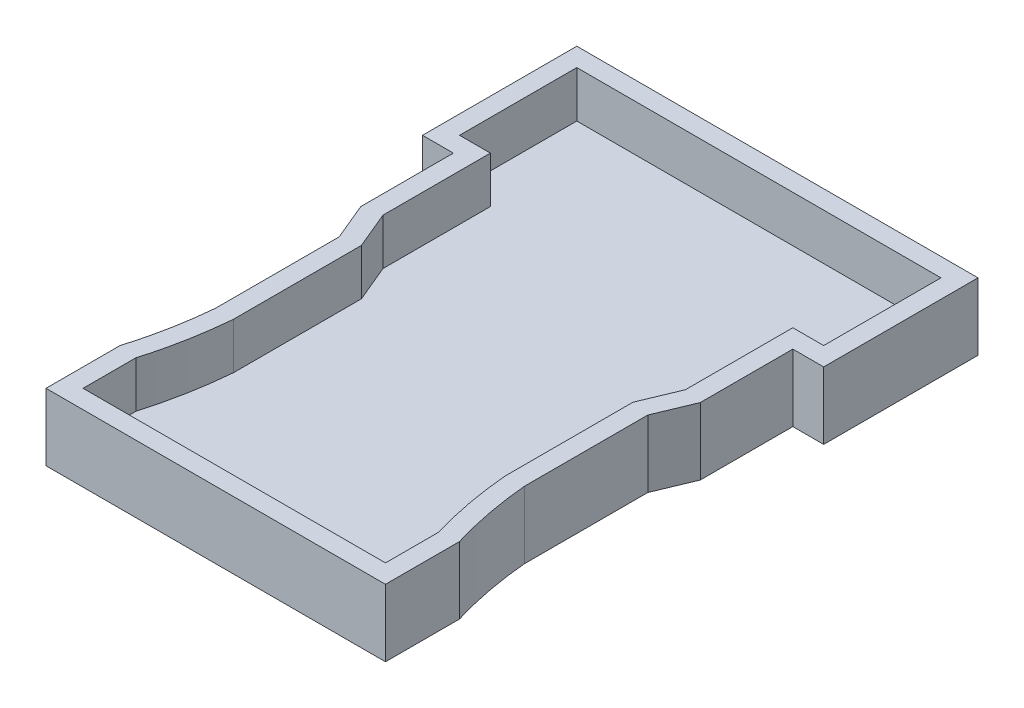
SolidWorks part; units mm, degrees
ref_plane "Front Plane" through (0, 0, 0) normal (0, 0, 1) x (1, 0, 0)
ref_plane "Top Plane" through (0, 0, 0) normal (0, 1, 0) x (1, 0, 0)
ref_plane "Right Plane" through (0, 0, 0) normal (1, 0, 0) x (0, 0, -1)
sketch "Sketch3" plane through (0, 0, 0) normal (0, 1, 0) x (1, 0, 0)
  line L0 (0, 76.2) -> (0, 1097.1298)
  line L2 (1088.6229, 0) -> (101.5999, 0)
  line L3 (1101.6, 0) -> (101.5999, 0)
  line L13 (55.0333, 42.3334) -> (8.4666, 42.3334)
  line L14 (101.5999, 0) -> (101.5999, -25.4)
  line L15 (97.3667, -35.56) -> (97.3667, -69.4266)
  line L16 (0, 0) -> (8.4666, 0)
  line L17 (0, 0) -> (0, 42.3334)
  line L18 (0, 42.3334) -> (110.0666, 42.3334)
  line L19 (110.0666, 0) -> (110.0666, 42.3334)
  line L20 (8.4666, 0) -> (-100.2964, 0)
  line L23 (8.4666, -25.4) -> (8.4666, 0)
  line L24 (12.6999, -35.56) -> (12.6999, -69.4266)
  line L31 (101.5999, -25.4) -> (97.3667, -35.56)
  line L32 (8.4666, -25.4) -> (12.6999, -35.56)
  line L33 (8.4667, -91.44) -> (8.4667, -111.76)
  line L35 (101.6, -91.44) -> (101.6, -111.76)
  line L36 (101.5999, 0) -> (110.0666, 0)
  line L43 (101.6, -111.76) -> (8.4667, -111.76)
  spline S0 degree 2 poles (12.6999, -69.4266) (11.6904, -80.7665) (8.4667, -91.44) knots 0 0 0 0.50454 0.50454 0.50454
  spline S1 degree 2 poles (97.3667, -69.4266) (98.3763, -80.7665) (101.6, -91.44) knots 0 0 0 0.50454 0.50454 0.50454
extrude "Boss-Extrude1" add sketch "Sketch3" along normal blind 18.415
ref_plane "Plane1" through (0, 18.415, 0) normal (0, 1, 0) x (1, 0, 0)
sketch "Sketch7" plane through (0, 18.415, 0) normal (0, 1, 0) x (1, 0, 0)
  line L108 (104.9866, 0) -> (104.9866, 42.3334)
  line L109 (104.9866, 5.08) -> (104.9866, 37.2534)
  line L119 (110.0666, 5.08) -> (96.5199, 5.08)
  line L120 (96.5199, 5.08) -> (96.5199, -24.384)
  line L121 (96.5199, -24.384) -> (92.2867, -34.544)
  line L122 (92.2867, -34.544) -> (92.2867, -69.6498)
  line L123 (96.52, -92.1816) -> (96.52, -106.68)
  line L124 (96.52, -106.68) -> (13.5467, -106.68)
  line L125 (13.5467, -106.68) -> (13.5467, -92.1816)
  line L126 (17.7799, -69.6498) -> (17.7799, -34.544)
  line L127 (17.7799, -34.544) -> (13.5466, -24.384)
  line L128 (13.5466, 5.08) -> (5.08, 5.08)
  line L129 (13.5466, -24.384) -> (13.5466, 5.08)
  line L130 (5.08, 5.08) -> (5.08, 37.2534)
  line L131 (5.08, 37.2534) -> (110.0666, 37.2534)
  line L132 (104.9866, 5.08) -> (96.5199, 5.08)
  line L133 (96.5199, 5.08) -> (96.5199, -24.384)
  line L134 (96.5199, -24.384) -> (92.2867, -34.544)
  line L135 (92.2867, -34.544) -> (92.2867, -69.6498)
  line L136 (96.52, -92.1816) -> (96.52, -106.68)
  line L137 (96.52, -106.68) -> (13.5467, -106.68)
  line L138 (13.5467, -106.68) -> (13.5467, -92.1816)
  line L139 (17.7799, -69.6498) -> (17.7799, -34.544)
  line L140 (17.7799, -34.544) -> (13.5466, -24.384)
  line L141 (13.5466, 5.08) -> (5.08, 5.08)
  line L142 (13.5466, -24.384) -> (13.5466, 5.08)
  line L143 (5.08, 5.08) -> (5.08, 37.2534)
  line L144 (5.08, 37.2534) -> (104.9866, 37.2534)
  spline S0 degree 3 poles (3911.899, 470.57) (-1077.9854, 1385.4816) (-1230.5852, -2078.8342) (3755.6061, 1260.0241) knots -42.197736 -42.197736 -42.197736 -42.197736 40.014806 40.014806 40.014806 40.014806 only from (92.2867, -69.6498) to (96.52, -92.1816)
  spline S1 degree 3 poles (-3645.4569, 1260.0036) (1340.6451, -2078.8155) (1188.0176, 1385.4885) (-3801.7952, 470.5409) knots -39.01404 -39.01404 -39.01404 -39.01404 43.197244 43.197244 43.197244 43.197244 only from (13.5467, -92.1816) to (17.7799, -69.6498)
  spline S2 degree 3 poles (92.2867, -69.6498) (92.959, -77.3684) (94.37, -84.8857) (96.52, -92.1816) knots 0 0 0 0 1 1 1 1
  spline S3 degree 3 poles (13.5467, -92.1816) (15.6967, -84.8857) (17.1076, -77.3684) (17.7799, -69.6498) knots 0 0 0 0 1 1 1 1
  dimension "D1" = 5.08
  dimension "D2" = 5.08
extrude "Cut-Extrude1" cut sketch "Sketch7" against normal blind 12.7 contours L132 L133 L134 L135 S2 L136 L137 L138 S3 L139 L140 L142 L141 L143 L144 L109
